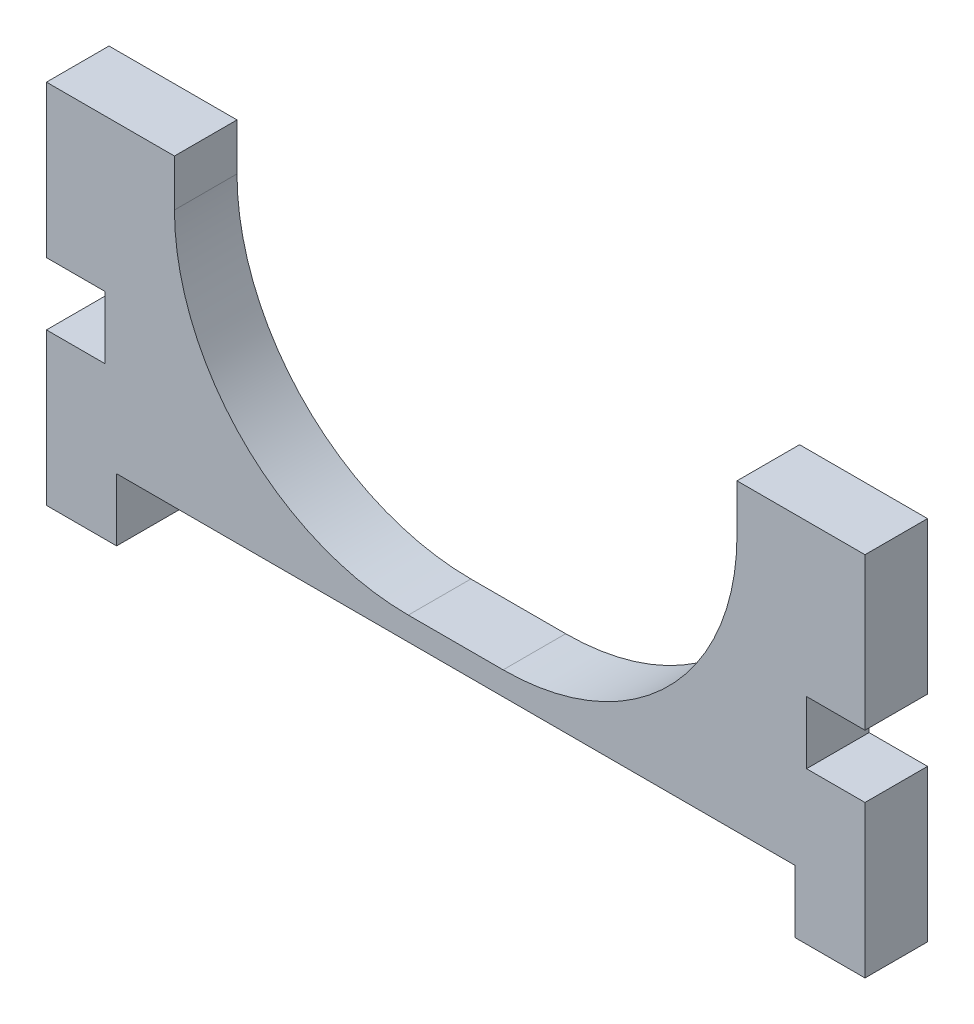
SolidWorks part; units mm, degrees
ref_plane "Front Plane" through (0, 0, 0) normal (0, 0, 1) x (1, 0, 0)
ref_plane "Top Plane" through (0, 0, 0) normal (0, 1, 0) x (1, 0, 0)
ref_plane "Right Plane" through (0, 0, 0) normal (1, 0, 0) x (0, 0, -1)
sketch "Model" plane through (0, 0, 0) normal (0, 0, 1) x (1, 0, 0)
  line L21 (0, 0) -> (0, 26) construction
  line L22 (-29, 0) -> (29, 0)
  line L23 (-35, -2.5009) -> (-35, 7.65)
  line L24 (-35, 26) -> (-24.055, 26)
  line L25 (35, -2.5009) -> (35, 7.65)
  line L26 (35, -5.35) -> (29, -5.35)
  line L27 (-4.055, 2) -> (4.055, 2)
  line L28 (-35, -2.5009) -> (-35, -5.35)
  line L29 (-35, -5.35) -> (-29, -5.35)
  line L30 (-29, 0) -> (-29, -5.35)
  line L31 (29, 0) -> (29, -5.35)
  line L32 (-24.055, 26) -> (-24.055, 22)
  line L33 (35, -2.5009) -> (35, -5.35)
  line L34 (35, 7.65) -> (30, 7.65)
  line L35 (-35, 13) -> (-30, 13)
  line L36 (35, 13) -> (35, 26)
  line L37 (-35, 7.65) -> (-30, 7.65)
  line L38 (-30, 13) -> (-30, 7.65)
  line L39 (30, 13) -> (30, 7.65)
  line L40 (35, 13) -> (30, 13)
  line L41 (24.055, 26) -> (35, 26)
  line L42 (-35, 13) -> (-35, 26)
  line L43 (24.055, 26) -> (24.055, 22)
  arc A2 (-24.055, 22) -> (-4.055, 2) centre (-4.055, 22) ccw
  arc A3 (24.055, 22) -> (4.055, 2) centre (4.055, 22) cw
  point P51 (0, 2)
  dimension "D21" = 20
  dimension "D13" = 5.35
  dimension "D14" = 6
  dimension "D15" = 70
  dimension "D16" = 26
  dimension "D17" = 5
  dimension "D18" = 5.35
  dimension "D19" = 13
  dimension "D20" = 2
  dimension "D22" = 10.945
extrude "Boss-Extrude1" add sketch "Model" along normal blind 5.35
equation "\"mdfthick\"=5.35"
equation "\"D13@Model\"=\"mdfthick\""
equation "\"D18@Model\"=\"mdfthick\""
equation "\"D1@Boss-Extrude1\"=\"mdfthick\""
